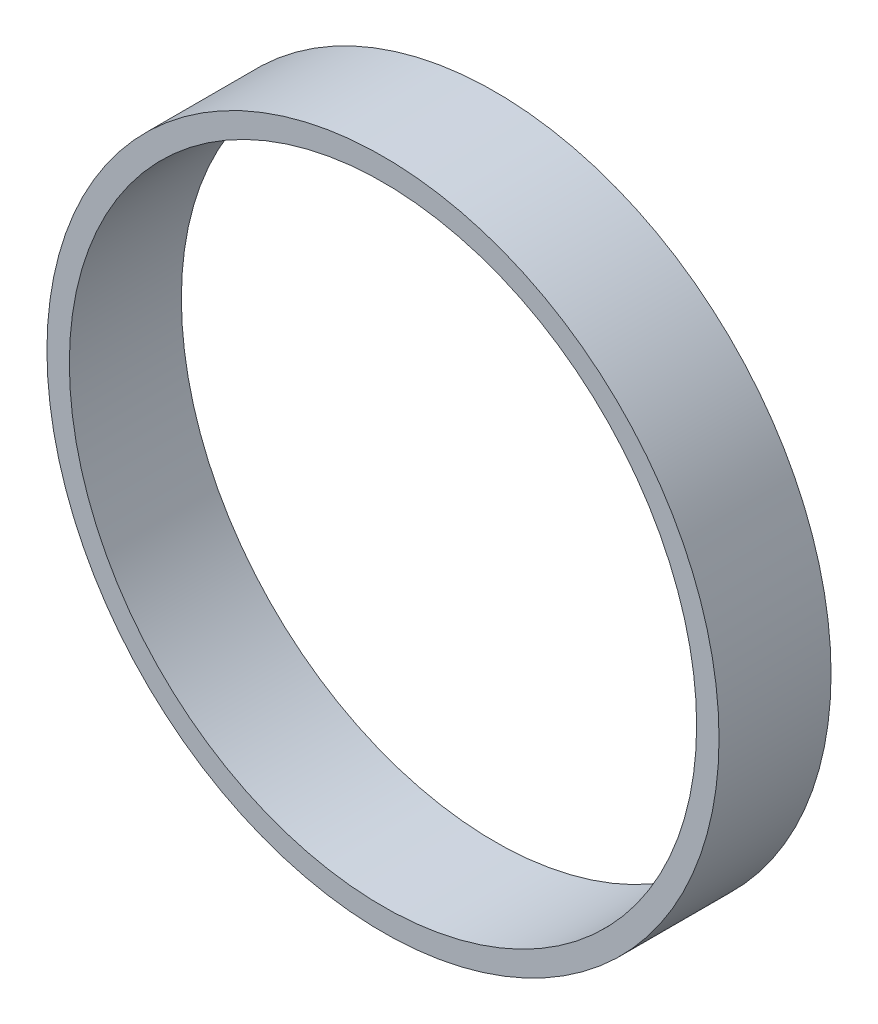
SolidWorks part; units mm, degrees
material "Калифорния"
ref_plane "Спереди" through (0, 0, 0) normal (0, 0, 1) x (1, 0, 0)
ref_plane "Сверху" through (0, 0, 0) normal (0, 1, 0) x (1, 0, 0)
ref_plane "Справа" through (0, 0, 0) normal (1, 0, 0) x (0, 0, -1)
sketch "Эскиз1" plane through (0, 0, 0) normal (0, 0, 1) x (1, 0, 0)
  line L0 (-81.0724, 33.5292) -> (-128.131, 41.9138) construction
  circle A0 centre (0, 0) radius 56
  circle A1 centre (0, 0) radius 60
extrude "Бобышка-Вытянуть1" add sketch "Эскиз1" along normal blind 20
